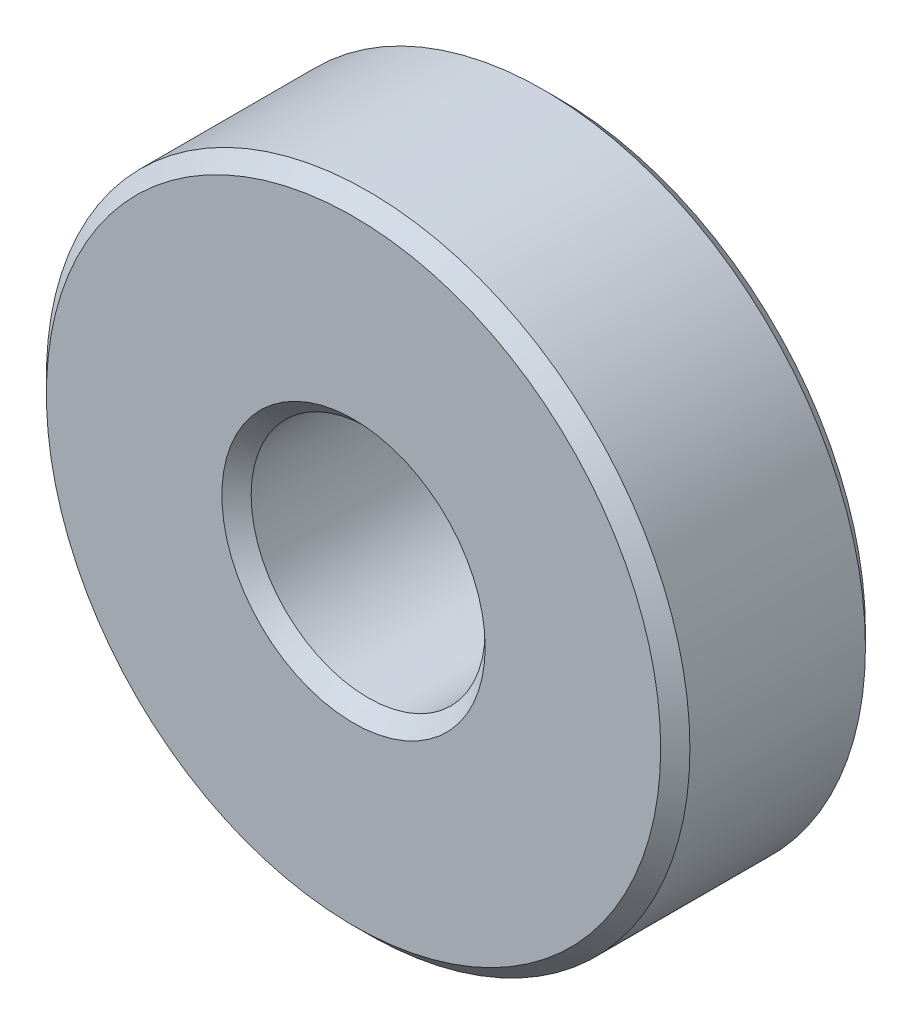
SolidWorks part; units mm, degrees
ref_plane "Płaszczyzna przednia" through (0, 0, 0) normal (0, 0, 1) x (1, 0, 0)
ref_plane "Płaszczyzna górna" through (0, 0, 0) normal (0, 1, 0) x (1, 0, 0)
ref_plane "Płaszczyzna prawa" through (0, 0, 0) normal (1, 0, 0) x (0, 0, -1)
sketch "Szkic1" plane through (0, 0, 0) normal (0, 0, 1) x (1, 0, 0)
  circle A0 centre (0, 0) radius 4
  circle A1 centre (0, 0) radius 11
  dimension "D1" = 8
  dimension "D2" = 22
extrude "Dodanie-wyciągnięcie1" add sketch "Szkic1" along normal blind 7
chamfer "Sfazowanie1" distance 0.5 angle 45 4 edges at (11, 0, 0) (4, 0, 7) (11, 0, 7) (4, 0, 0)
